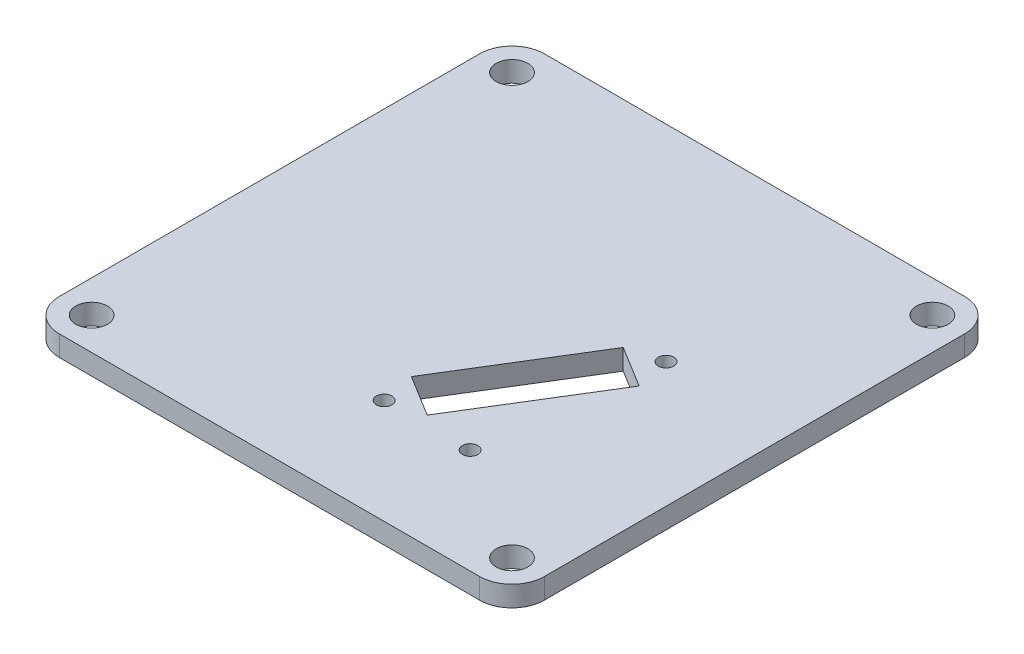
SolidWorks part; units mm, degrees
ref_plane "Front Plane" through (0, 0, 0) normal (0, 0, 1) x (1, 0, 0)
ref_plane "Top Plane" through (0, 0, 0) normal (0, 1, 0) x (1, 0, 0)
ref_plane "Right Plane" through (0, 0, 0) normal (1, 0, 0) x (0, 0, -1)
sketch "Sketch1" plane through (0, 0, 0) normal (0, 1, 0) x (1, 0, 0)
  line L1 (10, 0) -> (140, 0)
  line L2 (0, 10) -> (0, 140)
  line L3 (10, 150) -> (140, 150)
  line L4 (150, 10) -> (150, 140)
  arc A0 (140, 0) -> (150, 10) centre (140, 10) ccw
  arc A1 (10, 0) -> (0, 10) centre (10, 10) cw
  arc A2 (0, 140) -> (10, 150) centre (10, 140) cw
  arc A3 (140, 150) -> (150, 140) centre (140, 140) cw
  point P7 (150, 0)
  point P10 (0, 0)
  point P13 (0, 150)
  point P16 (150, 150)
  dimension "D3" = 10
  dimension "D1" = 150
  dimension "D2" = 150
extrude "Boss-Extrude1" add sketch "Sketch1" along normal blind 6.35
sketch "Sketch2" plane through (0, 6.35, 0) normal (0, 1, 0) x (1, 0, 0)
  line L0 (73.7734, 30) -> (106.7734, 30) construction
  line L1 (106.7734, 30) -> (115, 97) construction
  line L2 (115, 97) -> (73.7734, 30) construction
  line L3 (140, 150) -> (10, 150) construction
  line L4 (0, 140) -> (0, 10) construction
  line L5 (75.8916, 42.9833) -> (88.6668, 35.1224)
  line L6 (88.6668, 35.1224) -> (113.6278, 75.6881)
  line L7 (113.6278, 75.6881) -> (100.8525, 83.5489)
  line L8 (75.8916, 42.9833) -> (100.8525, 83.5489)
  line L9 (10, 0) -> (140, 0) construction
  line L10 (150, 10) -> (150, 140) construction
  circle A0 centre (78.0682, 32.4) radius 2.4
  circle A1 centre (104.6501, 32.4) radius 2.4
  circle A2 centre (111.2767, 86.3694) radius 2.4
  circle A3 centre (10, 140) radius 4.9
  circle A4 centre (10, 10) radius 4.9
  circle A5 centre (140, 140) radius 4.9
  circle A6 centre (140, 10) radius 4.9
  dimension "D6" = 4.8
  dimension "D7" = 4.8
  dimension "D8" = 4.8
  dimension "D14" = 9.8
  dimension "D15" = 9.8
  dimension "D16" = 9.8
  dimension "D17" = 9.8
  dimension "D20" = 10
  dimension "D1" = 97
  dimension "D2" = 33
  dimension "D3" = 67
  dimension "D4" = 30
  dimension "D5" = 35
  dimension "D9" = 15
  dimension "D10" = 47.63
  dimension "D11" = 5
  dimension "D12" = 7.865
  dimension "D13" = 7.873
  dimension "D18" = 10
  dimension "D19" = 10
  dimension "D21" = 10
  dimension "D22" = 10
  dimension "D23" = 10
  dimension "D24" = 10
  dimension "D25" = 10
extrude "Cut-Extrude1" cut sketch "Sketch2" against normal through all
sketch "Sketch4" plane through (0, 0, 0) normal (0, -1, 0) x (1, 0, 0)
  line L0 (88.3721, -63.2661) -> (101.1473, -55.4052) construction
  line L1 (100.8525, -83.5489) -> (75.8916, -42.9833) construction
  line L2 (88.6668, -35.1224) -> (113.6278, -75.6881) construction
